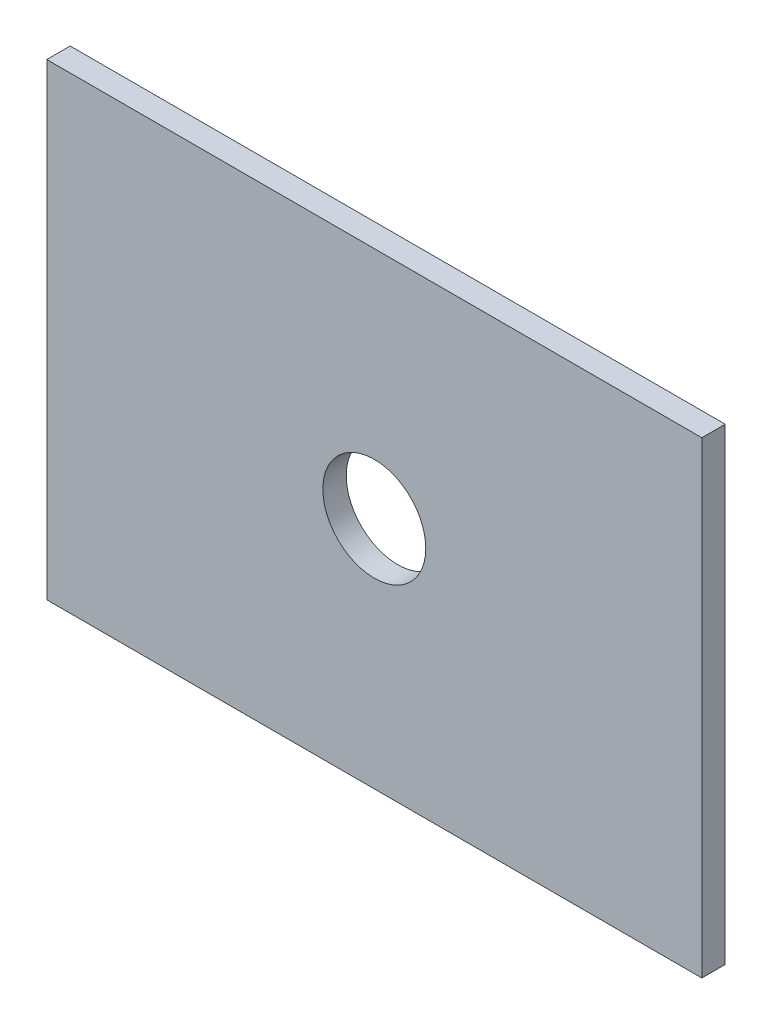
SolidWorks part; units mm, degrees
material "Perspex (TM) GS Acrylic Cast Sheet"
ref_plane "Ebene vorne" through (0, 0, 0) normal (0, 0, 1) x (1, 0, 0)
ref_plane "Ebene oben" through (0, 0, 0) normal (0, 1, 0) x (1, 0, 0)
ref_plane "Ebene rechts" through (0, 0, 0) normal (1, 0, 0) x (0, 0, -1)
sketch "Skizze1" plane through (0, 0, 0) normal (0, 0, 1) x (1, 0, 0)
  line L1 (-70, 50) -> (70, 50)
  line L2 (-70, 50) -> (-70, -50)
  line L3 (-70, -50) -> (70, -50)
  line L4 (70, 50) -> (70, -50)
  line L5 (-70, 50) -> (70, -50) construction
  line L6 (-70, -50) -> (70, 50) construction
  point P0 (0, 0)
  dimension "D1" = 140
  dimension "D2" = 100
extrude "Aufsatz-Linear austragen1" add sketch "Skizze1" along normal blind 5
sketch "Skizze2" plane through (0, 0, 5) normal (0, 0, 1) x (1, 0, 0)
  circle A0 centre (0, 0) radius 11
  dimension "D1" = 22
extrude "Schnitt-Linear austragen1" cut sketch "Skizze2" against normal through all
